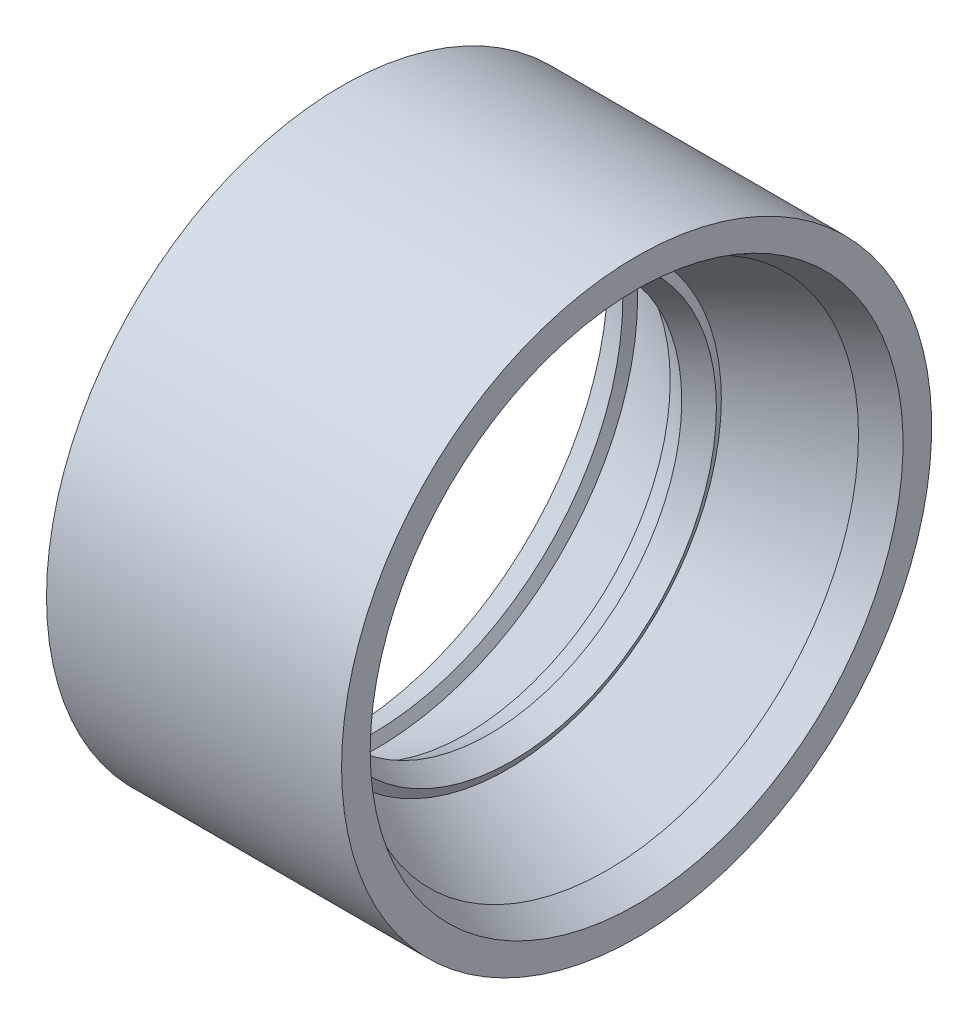
SolidWorks part; units mm, degrees
ref_plane "Front Plane" through (0, 0, 0) normal (0, 0, 1) x (1, 0, 0)
ref_plane "Top Plane" through (0, 0, 0) normal (0, 1, 0) x (1, 0, 0)
ref_plane "Right Plane" through (0, 0, 0) normal (1, 0, 0) x (0, 0, -1)
sketch "Sketch2" plane through (0, 0, 0) normal (0, 0, 1) x (1, 0, 0)
  line L0 (0, 20) -> (40, 20)
  line L4 (-13.6673, 60) -> (58.28, 60) construction
  line L8 (35.9751, 25.8944) -> (35.3043, 24.5528)
  line L9 (23.1305, 32.3167) -> (20, 33.882)
  line L12 (35.9751, 25.8944) -> (40, 23.882)
  line L13 (40, 23.882) -> (40, 20)
  line L16 (4.0249, 25.8944) -> (0, 23.882)
  line L17 (4.0249, 25.8944) -> (4.6957, 24.5528)
  line L18 (17.5403, 30.9751) -> (4.6957, 24.5528)
  line L20 (22.4597, 30.9751) -> (23.1305, 32.3167)
  line L22 (22.4597, 30.9751) -> (35.3043, 24.5528)
  line L23 (17.5403, 30.9751) -> (16.8695, 32.3167)
  line L25 (16.8695, 32.3167) -> (20, 33.882)
  line L27 (0, 23.882) -> (0, 20)
revolve "Revolve1" add sketch "Sketch2" angle 360 about L4
